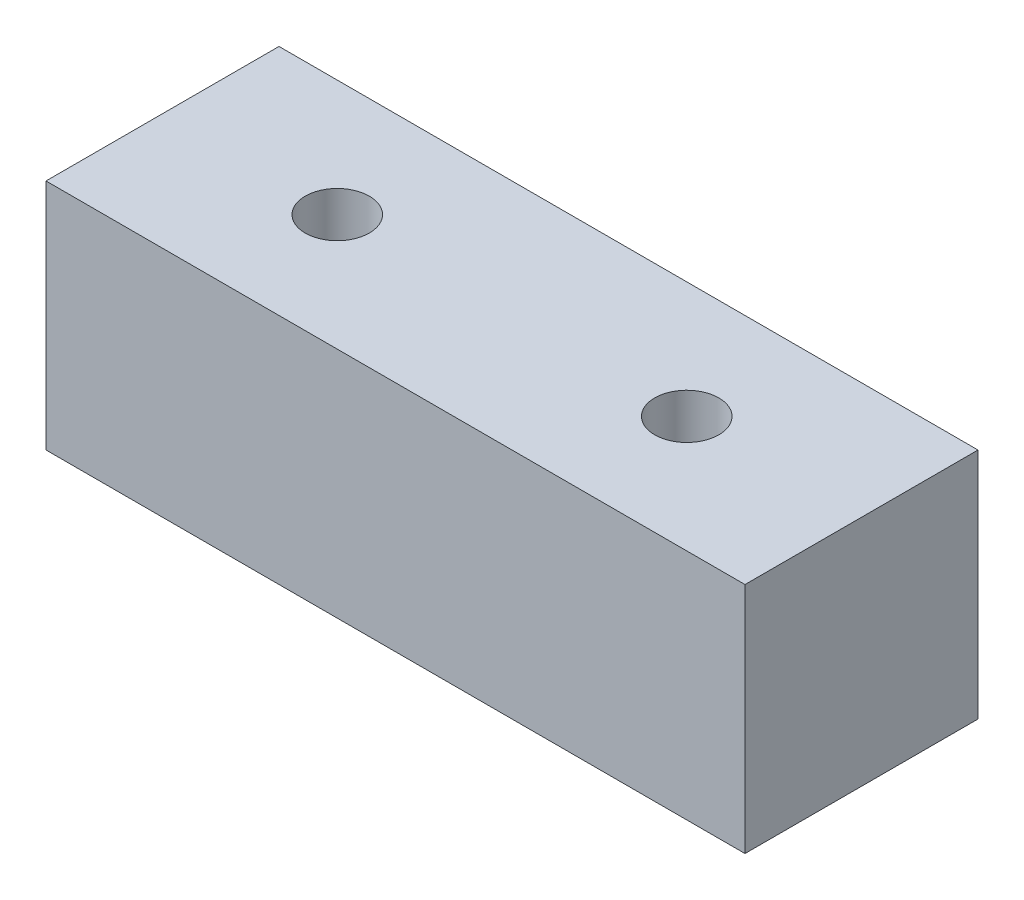
SolidWorks part; units mm, degrees
material "Plain Carbon Steel"
ref_plane "Front Plane" through (0, 0, 0) normal (0, 0, 1) x (1, 0, 0)
ref_plane "Top Plane" through (0, 0, 0) normal (0, 1, 0) x (1, 0, 0)
ref_plane "Right Plane" through (0, 0, 0) normal (1, 0, 0) x (0, 0, -1)
sketch "Sketch1" plane through (0, 0, 0) normal (1, 0, 0) x (0, 0, -1)
  line L1 (-10, -10) -> (10, -10)
  line L2 (-10, -10) -> (-10, 10)
  line L3 (-10, 10) -> (10, 10)
  line L4 (10, -10) -> (10, 10)
  line L5 (-10, -10) -> (10, 10) construction
  line L6 (-10, 10) -> (10, -10) construction
  point P0 (0, 0)
  dimension "D1" = 20
  dimension "D2" = 20
extrude "Boss-Extrude1" add sketch "Sketch1" along normal mid plane 60
sketch "Sketch2" plane through (0, 10, 0) normal (0, 1, 0) x (1, 0, 0)
  circle A0 centre (15, 0) radius 2.75
  dimension "D1" = 5.5
  dimension "D2" = 15
extrude "Cut-Extrude1" cut sketch "Sketch2" against normal through all
mirror "Mirror1" about plane through (0, 0, 0) normal (1, 0, 0) of "Cut-Extrude1"
